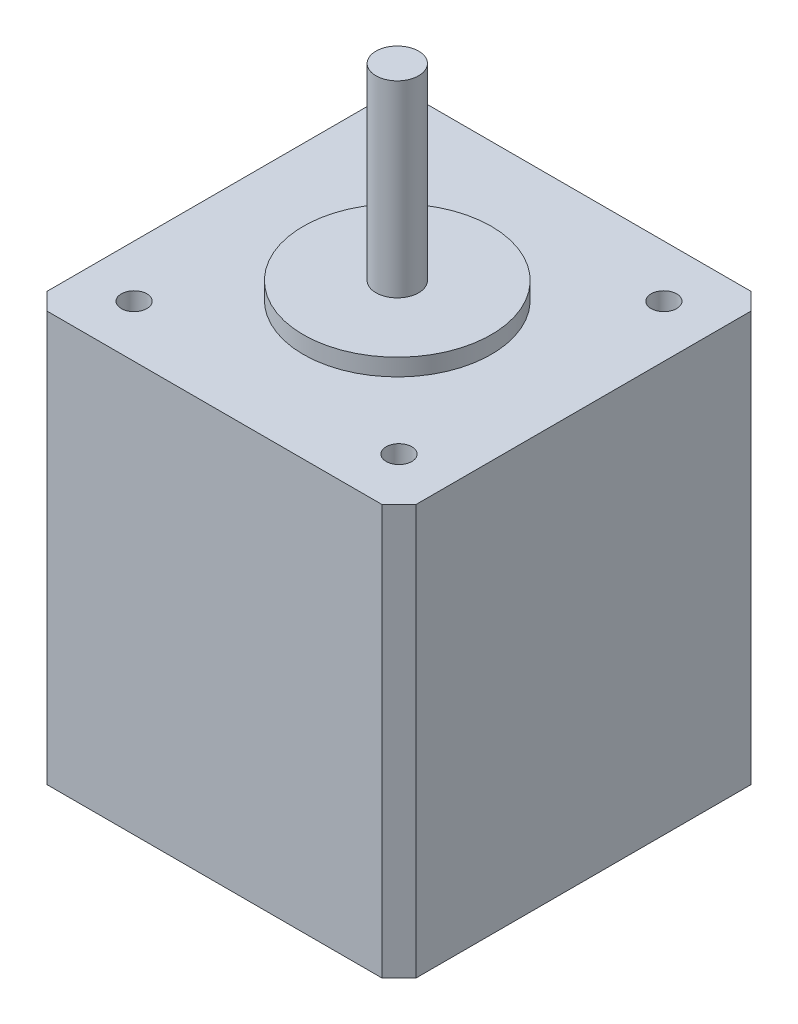
SolidWorks part; units mm, degrees
ref_plane "Front Plane" through (0, 0, 0) normal (0, 0, 1) x (1, 0, 0)
ref_plane "Top Plane" through (0, 0, 0) normal (0, 1, 0) x (1, 0, 0)
ref_plane "Right Plane" through (0, 0, 0) normal (1, 0, 0) x (0, 0, -1)
sketch "Sketch1" plane through (0, 0, 0) normal (0, 1, 0) x (1, 0, 0)
  line L1 (0, 0) -> (43.2, 0)
  line L2 (0, 0) -> (0, 43.2)
  line L3 (0, 43.2) -> (43.2, 43.2)
  line L4 (43.2, 0) -> (43.2, 43.2)
  circle A0 centre (6.1, 37.1) radius 1.5
  circle A1 centre (37.1, 37.1) radius 1.5
  circle A2 centre (37.1, 6.1) radius 1.5
  circle A3 centre (6.1, 6.1) radius 1.5
  dimension "D3" = 3
  dimension "D6" = 31
  dimension "D7" = 31
  dimension "D9" = 6.1
  dimension "D1" = 43.2
  dimension "D2" = 43.2
  dimension "D8" = 6.1
  dimension "D4" = 2
  dimension "D5" = 2
extrude "Boss-Extrude1" add sketch "Sketch1" along normal blind 48
chamfer "Chamfer1" distance 2 angle 45 4 edges at (0, 24, -43.2) (43.2, 24, -43.2) (43.2, 24, 0) (0, 24, 0)
sketch "Sketch2" plane through (0, 48, 0) normal (0, 1, 0) x (1, 0, 0)
  line L0 (2, 0) -> (41.2, 0) construction
  line L1 (43.2, 2) -> (43.2, 41.2) construction
  circle A0 centre (21.4, 21.6) radius 11
  dimension "D1" = 22
  dimension "D2" = 21.6
  dimension "D3" = 21.8
extrude "Boss-Extrude2" add sketch "Sketch2" along normal blind 2
sketch "Sketch3" plane through (0, 48, 0) normal (0, 1, 0) x (1, 0, 0)
  circle A0 centre (21.4, 21.6) radius 2.5
  dimension "D1" = 5
extrude "Boss-Extrude3" add sketch "Sketch3" along normal blind 24
